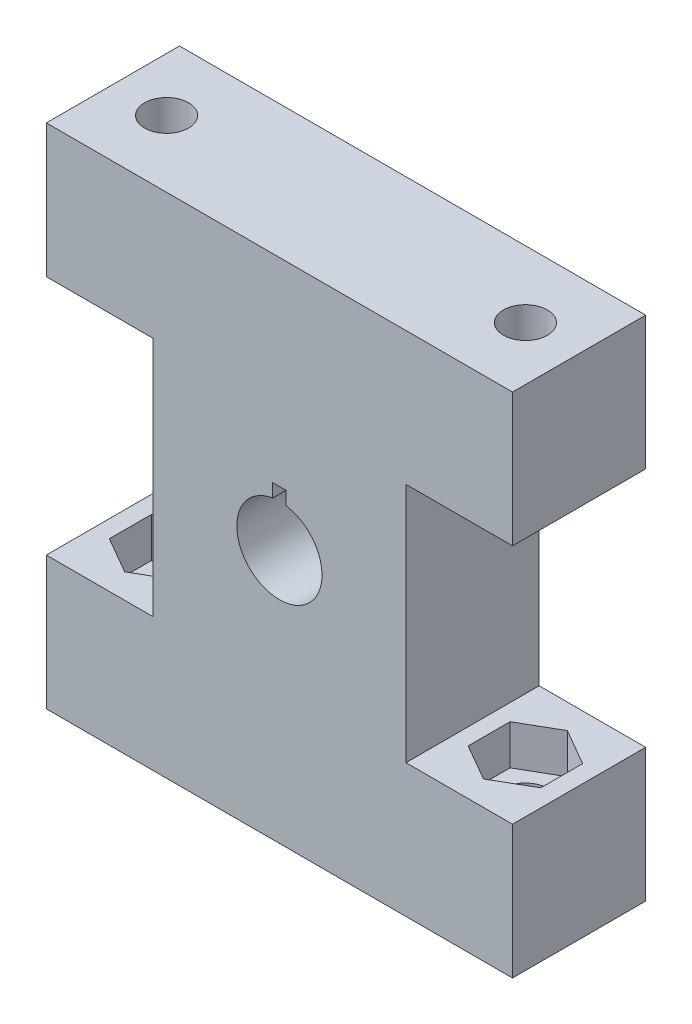
SolidWorks part; units mm, degrees
ref_plane "Front Plane" through (0, 0, 0) normal (0, 0, 1) x (1, 0, 0)
ref_plane "Top Plane" through (0, 0, 0) normal (0, 1, 0) x (1, 0, 0)
ref_plane "Right Plane" through (0, 0, 0) normal (1, 0, 0) x (0, 0, -1)
sketch "Sketch1" plane through (0, 0, 0) normal (0, 0, 1) x (1, 0, 0)
  line L1 (-17.5, 19.05) -> (17.5, 19.05)
  line L2 (-17.5, 19.05) -> (-17.5, -19.05)
  line L3 (-17.5, -19.05) -> (17.5, -19.05)
  line L4 (17.5, 19.05) -> (17.5, -19.05)
  point P4 (0, 19.05)
  point P6 (-17.5, 0)
  dimension "D1" = 38.1
  dimension "D2" = 35
extrude "Boss-Extrude1" add sketch "Sketch1" along normal blind 10
hole_wizard "Ø3.3 (3.3) Diameter Hole1" positions "Sketch2" profile "Sketch3" hole size "Ø3.3" standard "ANSI Metric" end condition through all
sketch "Sketch2" plane through (0, 19.05, 0) normal (0, 1, 0) x (1, 0, 0)
  line L0 (-17.5, -10) -> (-17.5, 0) construction
  line L1 (-13.47, -5) -> (13.47, -5) construction
  point P0 (-13.47, -5)
  point P2 (13.47, -5)
  point P7 (-17.5, -5)
  point P12 (0, -5)
  dimension "D1" = 26.94
sketch "Sketch3" plane through (-13.47, 19.05, 5) normal (1, 0, 0) x (0, 0, 1)
  line L0 (0, 0) -> (0, 38.1)
  line L1 (0, 38.1) -> (1.65, 38.1)
  line L2 (1.65, 38.1) -> (1.65, 0)
  line L5 (1.65, 0) -> (0, 0)
  line L11 (0, -6.35) -> (0, 107.95) construction
  dimension "Thru Hole Dia." = 3.3
  dimension "Thru Hole Depth" = 38.1
sketch "Sketch4" plane through (0, 0, 10) normal (0, 0, 1) x (1, 0, 0)
  line L0 (-17.5, -19.05) -> (17.5, -19.05) construction
  line L1 (17.5, 19.05) -> (-17.5, 19.05) construction
  circle A0 centre (0, 0) radius 3.2
  point P8 (0, 19.05)
  dimension "D1" = 6.4
  dimension "D2" = 19.05
extrude "Cut-Extrude1" cut sketch "Sketch4" against normal through all
sketch "Sketch5" plane through (0, 0, 0) normal (0, 0, -1) x (-1, 0, 0)
  line L0 (-17.5, -19.05) -> (-17.5, 19.05) construction
  line L1 (-17.5, 9.05) -> (-9.5, 9.05)
  line L2 (-17.5, 9.05) -> (-17.5, 0)
  line L3 (-17.5, 0) -> (-9.5, 0)
  line L4 (-9.5, 9.05) -> (-9.5, 0)
  line L5 (-17.5, 19.05) -> (17.5, 19.05) construction
  dimension "D1" = 10
  dimension "D2" = 8
extrude "Cut-Extrude2" cut sketch "Sketch5" against normal blind 10
sketch "Sketch6" plane through (0, 9.05, 0) normal (0, -1, 0) x (1, 0, 0)
  line L0 (17.5, 10) -> (17.5, 0) construction
  line L1 (16.195, 6.5733) -> (13.47, 8.1466)
  line L2 (13.47, 8.1466) -> (10.745, 6.5733)
  line L3 (10.745, 6.5733) -> (10.745, 3.4267)
  line L4 (10.745, 3.4267) -> (13.47, 1.8534)
  line L5 (13.47, 1.8534) -> (16.195, 3.4267)
  line L6 (16.195, 3.4267) -> (16.195, 6.5733)
  circle A0 centre (13.47, 5) radius 2.725 construction
  dimension "D1" = 5.45
extrude "Cut-Extrude3" cut sketch "Sketch6" against normal blind 3
mirror "Mirror2" about plane through (0, 0, 0) normal (1, 0, 0) of "Cut-Extrude3", "Cut-Extrude2" second plane through (0, 0, 0) second plane normal (0, 1, 0)
sketch "Sketch7" plane through (0, 0, 10) normal (0, 0, 1) x (1, 0, 0)
  line L1 (-0.5, 4.1607) -> (0.5, 4.1607)
  line L2 (-0.5, 4.1607) -> (-0.5, 3.1607)
  line L3 (-0.5, 3.1607) -> (0.5, 3.1607)
  line L4 (0.5, 4.1607) -> (0.5, 3.1607)
  circle A0 centre (0, 0) radius 3.2 construction
  point P4 (0, 3.1607)
  dimension "D1" = 1
  dimension "D2" = 1
extrude "Cut-Extrude4" cut sketch "Sketch7" against normal through all both and the other way through all
